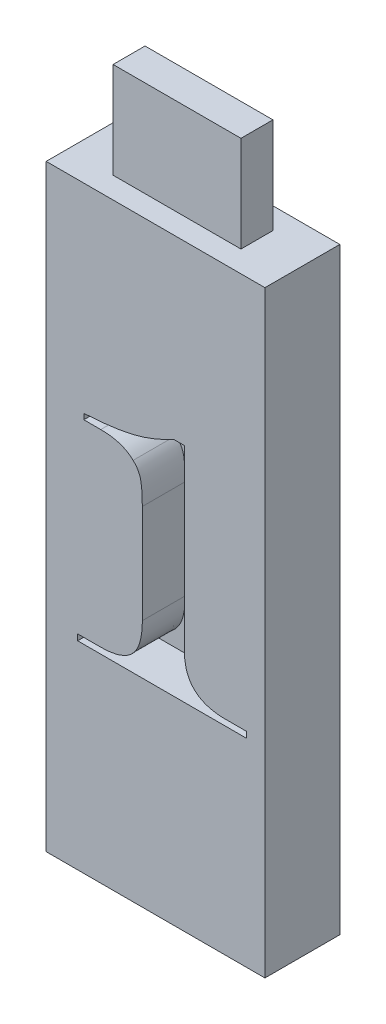
SolidWorks part; units mm, degrees
ref_plane "Front Plane" through (0, 0, 0) normal (0, 0, 1) x (1, 0, 0)
ref_plane "Top Plane" through (0, 0, 0) normal (0, 1, 0) x (1, 0, 0)
ref_plane "Right Plane" through (0, 0, 0) normal (1, 0, 0) x (0, 0, -1)
sketch "Sketch1" plane through (0, 0, 0) normal (0, 0, 1) x (1, 0, 0)
  line L1 (-8.69, -23.749) -> (8.69, -23.749)
  line L2 (-8.69, -23.749) -> (-8.69, 23.749)
  line L3 (-8.69, 23.749) -> (8.69, 23.749)
  line L4 (8.69, -23.749) -> (8.69, 23.749)
  line L5 (-8.69, -23.749) -> (8.69, 23.749) construction
  line L6 (-8.69, 23.749) -> (8.69, -23.749) construction
  point P0 (0, 0)
  dimension "D1" = 17.38
  dimension "D2" = 47.498
extrude "Boss-Extrude1" add sketch "Sketch1" along normal blind 5.95
sketch "Sketch2" plane through (0, 0, 5.95) normal (0, 0, 1) x (1, 0, 0)
  line L0 (0, 23.749) -> (0, -23.749) construction
  line L1 (8.69, 23.749) -> (-8.69, 23.749) construction
  line L2 (-8.69, -23.749) -> (8.69, -23.749) construction
  line L3 (0, -23.749) -> (0, 0) construction
  line L4 (0, 0) -> (-8.69, 0) construction
  line L5 (-8.69, 23.749) -> (-8.69, -23.749) construction
  line L6 (-8.69, 0) -> (8.69, 0) construction
  line L7 (8.69, -23.749) -> (8.69, 23.749) construction
  line L8 (-8.69, -23.749) -> (8.69, -23.749) construction
  line L9 (-8.69, -21.209) -> (8.69, -21.209) construction
  line L10 (-8.69, -18.669) -> (8.69, -18.669) construction
  line L11 (-8.69, -16.129) -> (8.69, -16.129) construction
  line L12 (-8.69, -13.589) -> (8.69, -13.589) construction
  line L13 (-8.69, -11.049) -> (8.69, -11.049) construction
  line L14 (-8.69, -8.509) -> (8.69, -8.509) construction
  line L15 (-8.69, -5.969) -> (8.69, -5.969) construction
  line L16 (-8.69, -3.429) -> (8.69, -3.429) construction
  line L17 (-8.69, -0.889) -> (8.69, -0.889) construction
  line L18 (-8.69, 1.651) -> (8.69, 1.651) construction
  line L19 (-8.69, 4.191) -> (8.69, 4.191) construction
  line L20 (-8.69, 6.731) -> (8.69, 6.731) construction
  line L21 (-8.69, 9.271) -> (8.69, 9.271) construction
  line L22 (-8.69, 11.811) -> (8.69, 11.811) construction
  line L23 (-8.69, 14.351) -> (8.69, 14.351) construction
  line L24 (-8.69, 16.891) -> (8.69, 16.891) construction
  line L25 (-8.69, 19.431) -> (8.69, 19.431) construction
  line L26 (-8.69, 21.971) -> (8.69, 21.971) construction
  line L27 (-8.69, 23.749) -> (-8.69, -23.749) construction
  line L28 (-6.15, 23.749) -> (-6.15, -23.749) construction
  line L29 (-3.61, 23.749) -> (-3.61, -23.749) construction
  line L30 (-1.07, 23.749) -> (-1.07, -23.749) construction
  line L31 (1.47, 23.749) -> (1.47, -23.749) construction
  line L32 (4.01, 23.749) -> (4.01, -23.749) construction
  line L33 (6.55, 23.749) -> (6.55, -23.749) construction
  text T0 "1\r\n" font "Engravers MT" height in points 72
  dimension "D1" = 19
  dimension "D2" = 2.54
  dimension "D4" = 2.54
  dimension "D3" = 7
extrude "Cut-Extrude1" cut sketch "Sketch2" against normal blind 3.41
sketch "Sketch3" plane through (0, 23.749, 0) normal (0, 1, 0) x (1, 0, 0)
  line L0 (0, 0) -> (0, -5.95) construction
  line L1 (8.69, -5.95) -> (-8.69, -5.95) construction
  line L2 (0, -5.95) -> (0, -2.975) construction
  line L3 (0, -2.975) -> (-8.69, -2.975) construction
  line L4 (-8.69, -5.95) -> (-8.69, 0) construction
  line L5 (-8.69, -2.975) -> (8.69, -2.975) construction
  line L6 (8.69, -5.95) -> (8.69, 0) construction
  line L8 (-5.08, -4.245) -> (5.08, -4.245)
  line L9 (-5.08, -4.245) -> (-5.08, -1.705)
  line L10 (-5.08, -1.705) -> (5.08, -1.705)
  line L11 (5.08, -4.245) -> (5.08, -1.705)
  line L12 (-5.08, -4.245) -> (5.08, -1.705) construction
  line L13 (-5.08, -1.705) -> (5.08, -4.245) construction
  dimension "D1" = 2.54
  dimension "D2" = 10.16
extrude "Boss-Extrude2" add sketch "Sketch3" along normal blind 7.62
